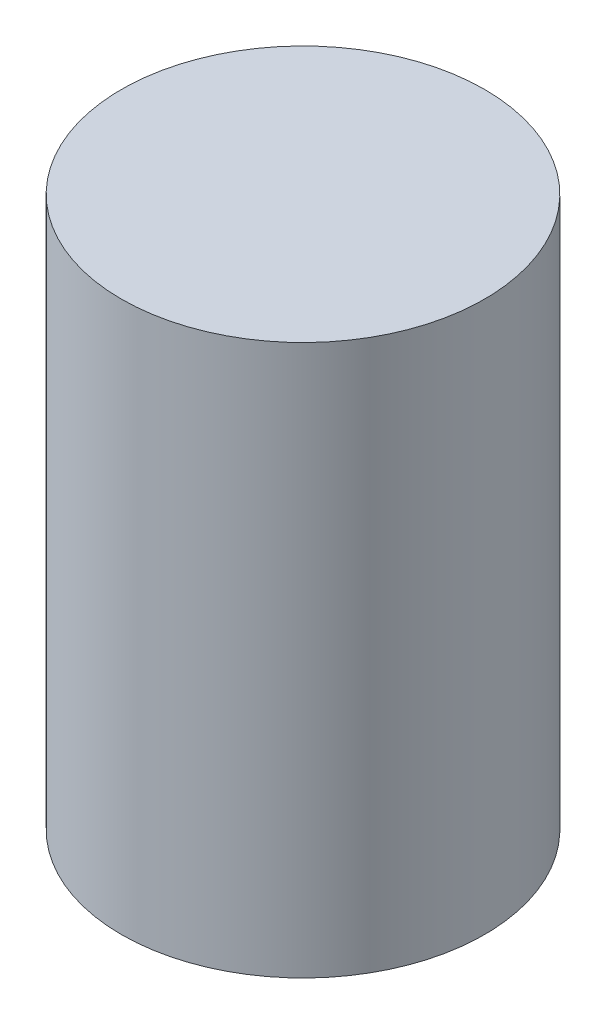
SolidWorks part; units mm, degrees
ref_plane "Спереди" through (0, 0, 0) normal (0, 0, 1) x (1, 0, 0)
ref_plane "Сверху" through (0, 0, 0) normal (0, 1, 0) x (1, 0, 0)
ref_plane "Справа" through (0, 0, 0) normal (1, 0, 0) x (0, 0, -1)
sketch "Эскиз1" plane through (0, 0, 0) normal (0, 1, 0) x (1, 0, 0)
  circle A0 centre (0, 0) radius 66
  dimension "D1" = 132
extrude "Бобышка-Вытянуть1" add sketch "Эскиз1" along normal blind 200
